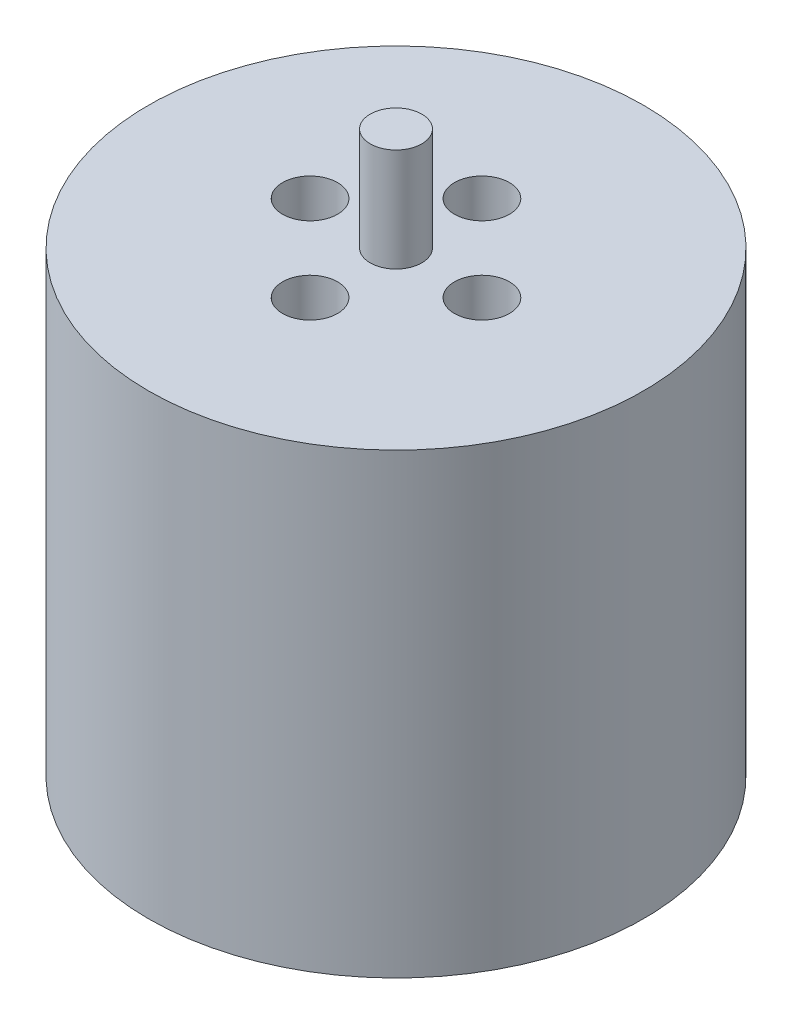
SolidWorks part; units mm, degrees
ref_plane "Front Plane" through (0, 0, 0) normal (0, 0, 1) x (1, 0, 0)
ref_plane "Top Plane" through (0, 0, 0) normal (0, 1, 0) x (1, 0, 0)
ref_plane "Right Plane" through (0, 0, 0) normal (1, 0, 0) x (0, 0, -1)
sketch "Sketch1" plane through (0, 0, 0) normal (0, 1, 0) x (1, 0, 0)
  circle A0 centre (0, 0) radius 7.2
  dimension "D1" = 14.4
extrude "Boss-Extrude1" add sketch "Sketch1" along normal mid plane 13.3
sketch "Sketch2" plane through (0, -6.65, 0) normal (0, -1, 0) x (1, 0, 0)
  circle A0 centre (0, 0) radius 0.75
  dimension "D1" = 1.5
extrude "Boss-Extrude2" add sketch "Sketch2" along normal blind 1
sketch "Sketch3" plane through (0, 6.65, 0) normal (0, 1, 0) x (1, 0, 0)
  circle A0 centre (0, 0) radius 0.75
  dimension "D1" = 1.5
extrude "Boss-Extrude3" add sketch "Sketch3" along normal blind 3
sketch "Sketch4" plane through (0, -6.65, 0) normal (0, -1, 0) x (1, 0, 0)
  circle A0 centre (0, 4.5) radius 0.8
  circle A1 centre (4.5, 0) radius 0.8
  circle A2 centre (0, -4.5) radius 0.8
  circle A3 centre (-4.5, 0) radius 0.8
  point P8 (0, 0)
  point P11 (0, 0)
  dimension "D1" = 1.6
  dimension "D2" = 9
  dimension "D3" = 9
  dimension "D4" = 4.5
  dimension "D5" = 4.5
extrude "Cut-Extrude1" cut sketch "Sketch4" against normal blind 2
sketch "Sketch5" plane through (0, 6.65, 0) normal (0, 1, 0) x (1, 0, 0)
  circle A0 centre (2.5, 0) radius 0.8
  circle A1 centre (0, -2.5) radius 0.8
  circle A2 centre (-2.5, 0) radius 0.8
  circle A3 centre (0, 2.5) radius 0.8
  circle A4 centre (0, 0) radius 2.5 construction
  point P8 (0, 0)
  point P10 (0, 0)
  point P11 (0, 0)
  point P14 (0, 0)
  point P15 (0, 0)
  dimension "D1" = 1.6
  dimension "D2" = 5
extrude "Cut-Extrude2" cut sketch "Sketch5" against normal blind 2
equation "\"D3@Sketch4\"=\"D2@Sketch4\""
equation "\"D4@Sketch4\"=\"D2@Sketch4\"/2"
equation "\"D5@Sketch4\"=\"D4@Sketch4\""
